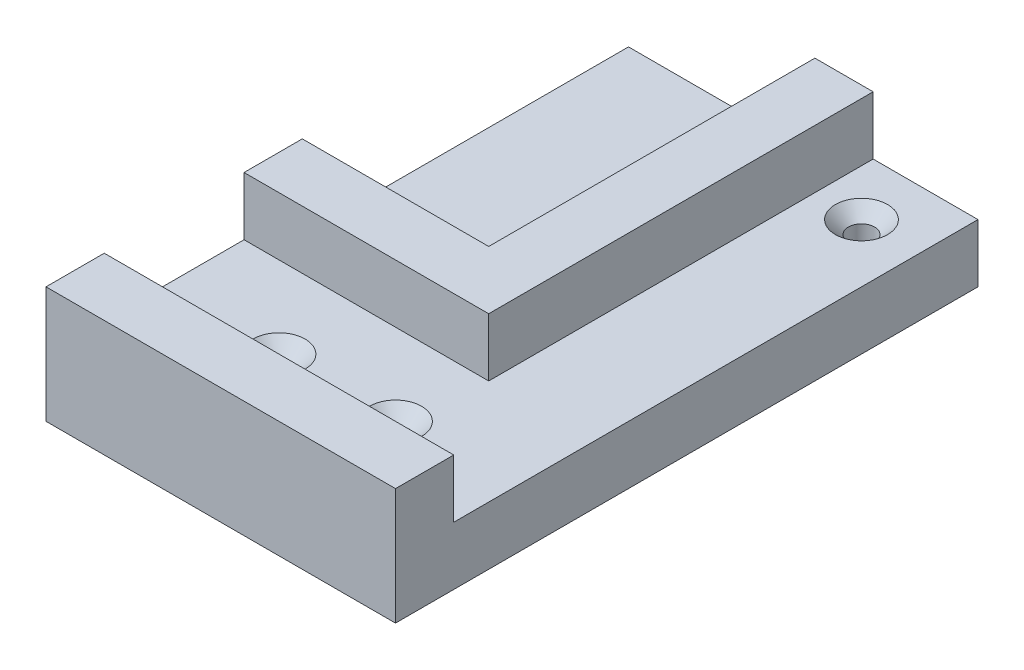
SolidWorks part; units mm, degrees
ref_plane "Front Plane" through (0, 0, 0) normal (0, 0, 1) x (1, 0, 0)
ref_plane "Top Plane" through (0, 0, 0) normal (0, 1, 0) x (1, 0, 0)
ref_plane "Right Plane" through (0, 0, 0) normal (1, 0, 0) x (0, 0, -1)
sketch "Sketch1" plane through (0, 0, 0) normal (0, 1, 0) x (1, 0, 0)
  line L1 (-30, -50) -> (30, -50)
  line L2 (-30, -50) -> (-30, 50)
  line L3 (-30, 50) -> (30, 50)
  line L4 (30, -50) -> (30, 50)
  line L5 (-30, -50) -> (30, 50) construction
  line L6 (-30, 50) -> (30, -50) construction
  point P0 (0, 0)
  dimension "D1" = 100
  dimension "D2" = 60
extrude "Boss-Extrude1" add sketch "Sketch1" along normal blind 20
sketch "Sketch2" plane through (0, 20, 0) normal (0, 1, 0) x (1, 0, 0)
  line L1 (-30, 50) -> (2, 50)
  line L2 (-30, 50) -> (-30, -6)
  line L3 (-30, -6) -> (2, -6)
  line L4 (2, 50) -> (2, -6)
  dimension "D1" = 32
  dimension "D2" = 56
extrude "Cut-Extrude1" cut sketch "Sketch2" against normal blind 14.325
sketch "Sketch3" plane through (0, 20, 0) normal (0, 1, 0) x (1, 0, 0)
  line L0 (2, -6) -> (2, 50) construction
  line L1 (-30, 50) -> (12, 50)
  line L2 (-30, 50) -> (-30, -16)
  line L3 (-30, -16) -> (12, -16)
  line L4 (12, 50) -> (12, -16)
  line L5 (-30, -6) -> (2, -6) construction
  line L6 (-30, -40) -> (30, -40)
  line L7 (-30, -6) -> (-30, -50) construction
  line L8 (30, -50) -> (30, 50) construction
  line L9 (-30, -50) -> (30, -50) construction
  line L10 (-30, -16) -> (-30, -40)
  line L11 (12, 50) -> (30, 50)
  line L12 (30, 50) -> (30, -40)
  line M6 (30, 50) -> (2, 50)
  line M9 (-30, -6) -> (-30, -50)
  line M11 (30, -50) -> (30, 50)
  dimension "D1" = 10
  dimension "D2" = 10
  dimension "D3" = 10
extrude "Cut-Extrude2" cut sketch "Sketch3" against normal blind 10 contours L6 L4 L3 M9 M11 M6
hole_wizard "CSK for M4 SFHCS1" positions "Sketch4" profile "Sketch5" countersink size "M4" standard "ANSI Metric" end condition through all
sketch "Sketch4" plane through (0, 10, 0) normal (0, 1, 0) x (1, 0, 0)
  line L0 (30, -40) -> (30, 50) construction
  line L1 (-30, -50) -> (30, -50) construction
  point P13 (20, 40)
  point P15 (10, -30)
  point P17 (-10, -30)
  point P20 (0, 0)
  dimension "D1" = 20
  dimension "D2" = 20
  dimension "D3" = 20
  dimension "D4" = 10
  dimension "D5" = 90
sketch "Sketch5" plane through (20, 10, -40) normal (1, 0, 0) x (0, 0, 1)
  line L0 (0, 0) -> (0, 10)
  line L1 (0, 10) -> (2.25, 10)
  line L2 (2.25, 10) -> (2.25, 2.23)
  line L3 (2.25, 2.23) -> (4.48, 0)
  line L5 (4.48, 0) -> (0, 0)
  line L6 (-2.25, 2.23) -> (-4.48, 0) construction
  line L11 (0, -6.35) -> (0, 107.95) construction
  dimension "Thru Hole Dia." = 4.5
  dimension "Thru Hole Depth" = 10
  dimension "Near C'Sink Dia." = 8.96
  dimension "Near C'Sink Angle" = 90
